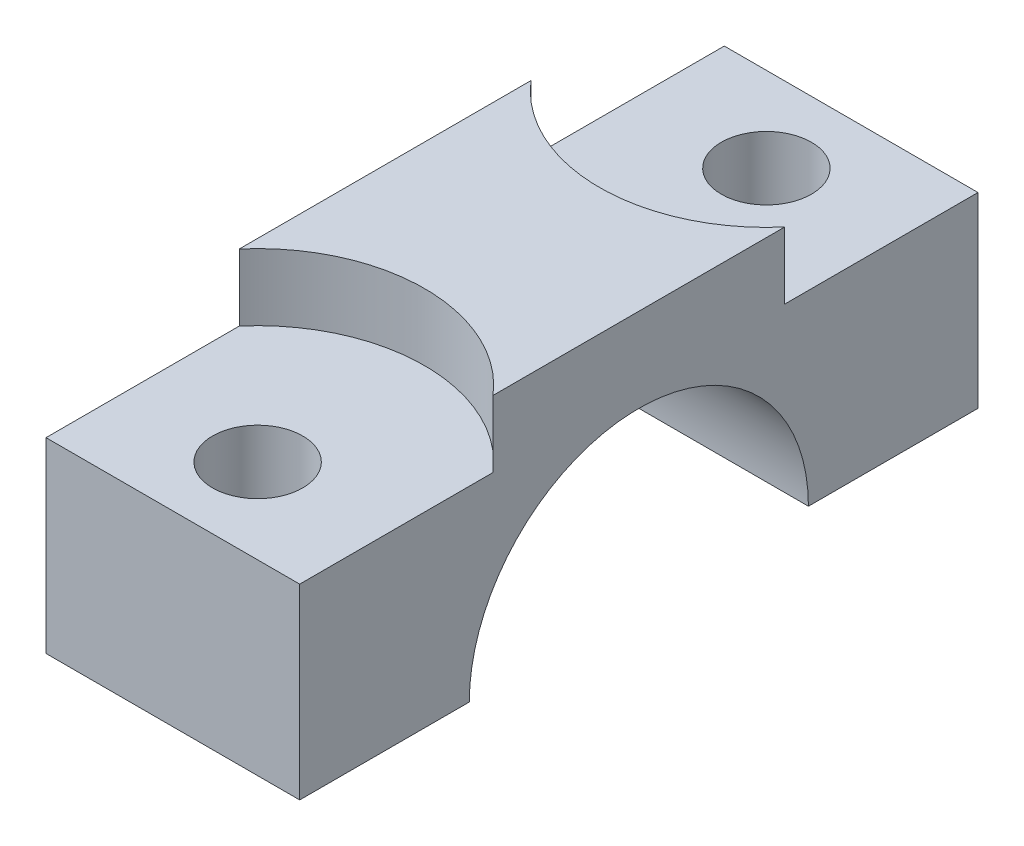
SolidWorks part; units mm, degrees
ref_plane "Front Plane" through (0, 0, 0) normal (0, 0, 1) x (1, 0, 0)
ref_plane "Top Plane" through (0, 0, 0) normal (0, 1, 0) x (1, 0, 0)
ref_plane "Right Plane" through (0, 0, 0) normal (1, 0, 0) x (0, 0, -1)
sketch "Sketch1" plane through (0, 0, 0) normal (1, 0, 0) x (0, 0, -1)
  line L0 (12.7, 0) -> (25.4, 0)
  line L1 (-25.4, 19) -> (25.4, 19)
  line L2 (-25.4, 19) -> (-25.4, 0)
  line L3 (-25.4, 0) -> (-12.7, 0)
  line L4 (25.4, 19) -> (25.4, 0)
  arc A0 (12.7, 0) -> (-12.7, 0) centre (0, 0) ccw
  point P5 (0, 0)
  point P8 (0, 0)
  dimension "D3" = 12.7
  dimension "D1" = 19
  dimension "D2" = 50.8
extrude "Boss-Extrude1" add sketch "Sketch1" along normal mid plane 19
sketch "Sketch2" plane through (0, 0, 0) normal (0, -1, 0) x (1, 0, 0)
  line L0 (-9.5, 19.05) -> (9.5, 19.05) construction
  line L1 (-9.5, 25.4) -> (-9.5, 12.7) construction
  line L2 (9.5, 25.4) -> (9.5, 12.7) construction
  line L3 (-9.5, -19.05) -> (9.5, -19.05) construction
  line L4 (-9.5, -12.7) -> (-9.5, -25.4) construction
  point P10 (0, 19.05)
  point P11 (0, -19.05)
  point P13 (0, 0)
hole_wizard "CBORE for M12 Hex Head Cap Screw1" positions "Sketch3" profile "Sketch4" counterbore size "M12" standard "ISO"
sketch "Sketch3" plane through (0, 19, 0) normal (0, 1, 0) x (1, 0, 0)
  point P0 (0, 19.05)
  point P3 (0, -19.05)
sketch "Sketch4" plane through (0, 19, -19.05) normal (1, 0, 0) x (0, 0, 1)
  line L0 (0, 0) -> (0, 326.39)
  line L1 (0, 326.39) -> (3.375, 326.39)
  line L2 (3.375, 326.39) -> (3.375, 5)
  line L3 (3.375, 5) -> (12.5, 5)
  line L4 (12.5, 5) -> (12.5, 0)
  line L5 (12.5, 0) -> (0, 0)
  line L10 (0, 326.39) -> (-3.375, 326.39) construction
  line L11 (0, -6.35) -> (0, 107.95) construction
  dimension "Hole Dia." = 6.75
  dimension "Hole Depth" = 326.39
  dimension "C'Bore Dia." = 25
  dimension "C'Bore Depth" = 5
  dimension "Drill Angle" = 180
